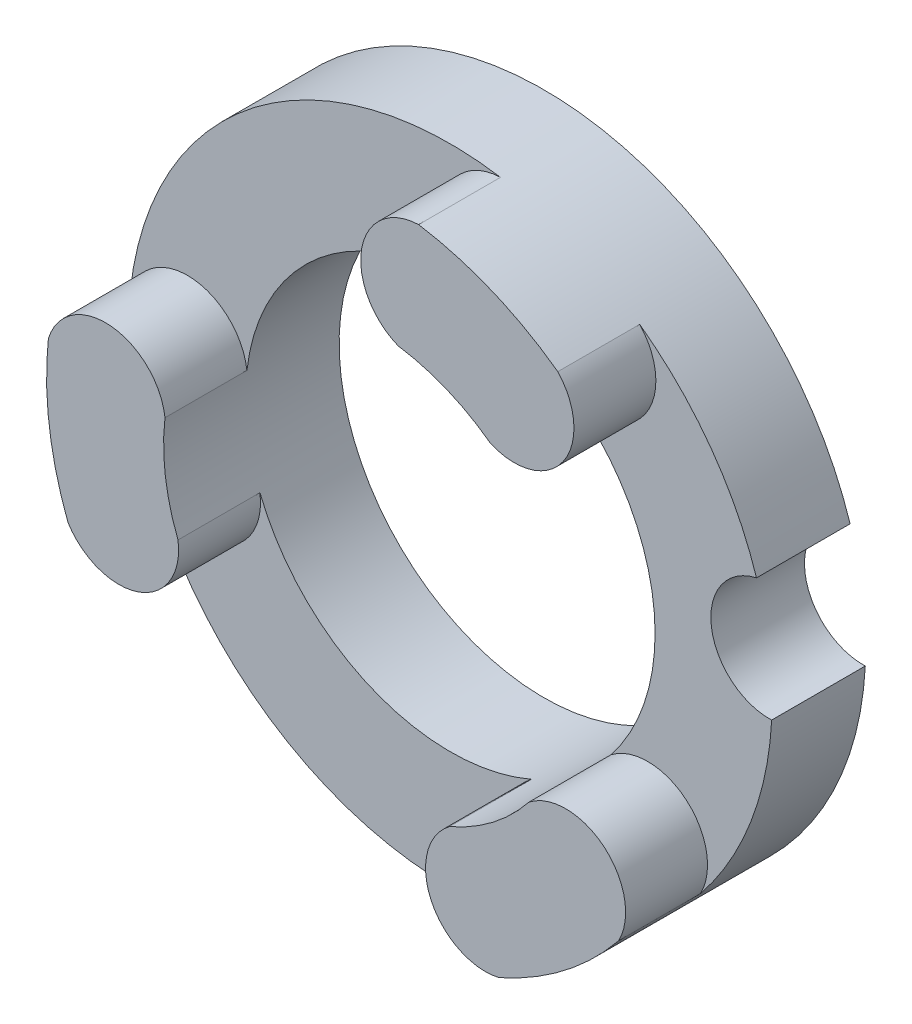
SolidWorks part; units mm, degrees
ref_plane "Front Plane" through (0, 0, 0) normal (0, 0, 1) x (1, 0, 0)
ref_plane "Top Plane" through (0, 0, 0) normal (0, 1, 0) x (1, 0, 0)
ref_plane "Right Plane" through (0, 0, 0) normal (1, 0, 0) x (0, 0, -1)
sketch "Sketch1" plane through (0, 0, 0) normal (0, 0, 1) x (1, 0, 0)
  circle A0 centre (0, 0) radius 27.5
  circle A1 centre (0, 0) radius 17.5
  dimension "D1" = 55
  dimension "D2" = 10
extrude "Boss-Extrude1" add sketch "Sketch1" along normal blind 8
sketch "Sketch2" plane through (0, 0, 8) normal (0, 0, 1) x (1, 0, 0)
  circle A0 centre (0, 0) radius 22.5
  arc A1 (12.4569, 18.737) -> (4.4569, 22.0542) centre (0, 0) ccw construction
  arc A2 (15.2867, 22.9935) -> (5.4693, 27.0642) centre (0, 0) ccw
  arc A3 (9.6271, 14.4806) -> (3.4444, 17.0442) centre (0, 0) ccw
  arc A4 (9.6271, 14.4806) -> (15.2867, 22.9935) centre (12.4569, 18.737) ccw
  arc A5 (5.4693, 27.0642) -> (3.4444, 17.0442) centre (4.4569, 22.0542) ccw
  arc A6 (7.727, -15.5776) -> (13.0385, -11.505) centre (0, 0) ccw
  arc A7 (7.727, -15.5776) -> (12.2696, -24.7354) centre (9.9983, -20.1565) ccw
  arc A8 (20.7036, -18.2687) -> (13.0385, -11.505) centre (16.871, -14.8868) ccw
  arc A9 (12.2696, -24.7354) -> (20.7036, -18.2687) centre (0, 0) ccw
  arc A10 (9.9983, -20.1565) -> (16.871, -14.8868) centre (0, 0) ccw construction
  arc A11 (-17.3541, 1.097) -> (-16.4829, -5.5391) centre (0, 0) ccw
  arc A12 (-17.3541, 1.097) -> (-27.5563, 1.7419) centre (-22.4552, 1.4194) ccw
  arc A13 (-26.1729, -8.7955) -> (-16.4829, -5.5391) centre (-21.3279, -7.1673) ccw
  arc A14 (-27.5563, 1.7419) -> (-26.1729, -8.7955) centre (0, 0) ccw
  arc A15 (-22.4552, 1.4194) -> (-21.3279, -7.1673) centre (0, 0) ccw construction
  point P6 (8.618, 20.7841)
  point P15 (13.6906, -17.8555)
  point P22 (-22.3086, -2.9287)
  point P27 (0, 0)
  dimension "D1" = 45
  dimension "D3" = 8
  dimension "D2" = 3
extrude "Boss-Extrude2" add sketch "Sketch2" along normal blind 7 contours A0 A13 A6 A12 | A1 A13 A0 A12 | A1 A5 A0 A4 | A0 A5 A6 A4 | A1 A8 A0 A7 | A0 A8 A6 A7
sketch "Sketch4" plane through (0, 0, 8) normal (0, 0, 1) x (1, 0, 0)
  circle A0 centre (27.266, 3.5795) radius 5
  arc A1 (21.3771, -17.2994) -> (16.1876, 22.2309) centre (0, 0) ccw construction
  dimension "D1" = 10
extrude "Cut-Extrude1" cut sketch "Sketch4" against normal through all
